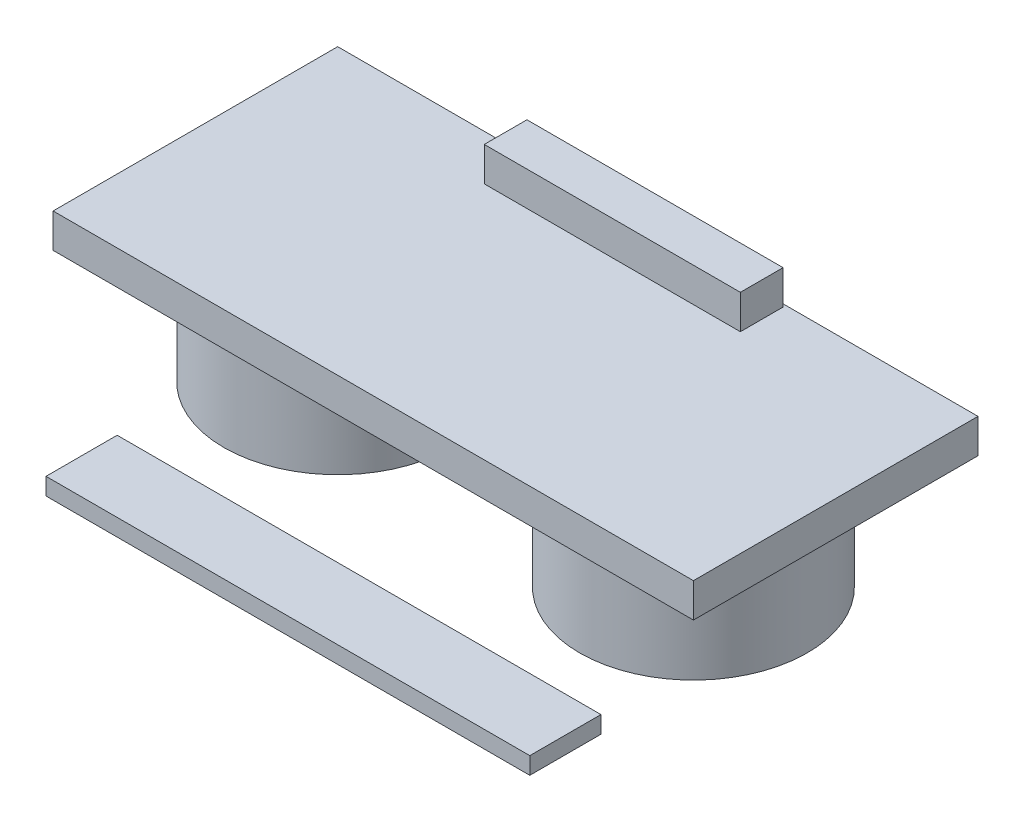
SolidWorks part; units mm, degrees
ref_plane "前视基准面" through (0, 0, 0) normal (0, 0, 1) x (1, 0, 0)
ref_plane "上视基准面" through (0, 0, 0) normal (0, 1, 0) x (1, 0, 0)
ref_plane "右视基准面" through (0, 0, 0) normal (1, 0, 0) x (0, 0, -1)
other "Configuration Table"
sketch "草图1" plane through (0, 0, 0) normal (0, 0, 1) x (1, 0, 0)
  line L1 (-22.5, -1.2) -> (22.5, -1.2)
  line L2 (-22.5, -1.2) -> (-22.5, 1.2)
  line L3 (-22.5, 1.2) -> (22.5, 1.2)
  line L4 (22.5, -1.2) -> (22.5, 1.2)
  line L5 (-22.5, -1.2) -> (22.5, 1.2) construction
  line L6 (-22.5, 1.2) -> (22.5, -1.2) construction
  point P0 (0, 0)
extrude "HC-SR04 PCB - 45 x 20 mm" add sketch "草图1" along normal blind 20 from offset 10 separate body
sketch "草图2" plane through (0, 0, 0) normal (0, 1, 0) x (1, 0, 0)
  circle A0 centre (-12.5, 0) radius 8
extrude "left ultrasonic transducer eye - dia 16 mm" add sketch "草图2" along normal blind 8 from offset 9.2 separate body
sketch "草图3" plane through (0, 0, 0) normal (0, 1, 0) x (1, 0, 0)
  circle A0 centre (12.5, 0) radius 8
extrude "right ultrasonic transducer eye - dia 16 mm" add sketch "草图3" along normal blind 8 from offset 9.2 separate body
sketch "草图4" plane through (0, 0, 0) normal (0, 0, 1) x (1, 0, 0)
  line L1 (-9, 0.4) -> (9, 0.4)
  line L2 (-9, 0.4) -> (-9, 3.6)
  line L3 (-9, 3.6) -> (9, 3.6)
  line L4 (9, 0.4) -> (9, 3.6)
  line L5 (-9, 0.4) -> (9, 3.6) construction
  line L6 (-9, 3.6) -> (9, 0.4) construction
  point P0 (0, 2)
extrude "4 pin header block" add sketch "草图4" along normal blind 3 from offset 9.8 separate body
sketch "草图5" plane through (0, 0, 0) normal (0, 0, 1) x (1, 0, 0)
  line L1 (-17, -10.4) -> (17, -10.4)
  line L2 (-17, -10.4) -> (-17, -9.2)
  line L3 (-17, -9.2) -> (17, -9.2)
  line L4 (17, -10.4) -> (17, -9.2)
  line L5 (-17, -10.4) -> (17, -9.2) construction
  line L6 (-17, -9.2) -> (17, -10.4) construction
  point P0 (0, -9.8)
extrude "sensor label plate - HC-SR04 45x20" add sketch "草图5" along normal blind 5 from offset 11 separate body
